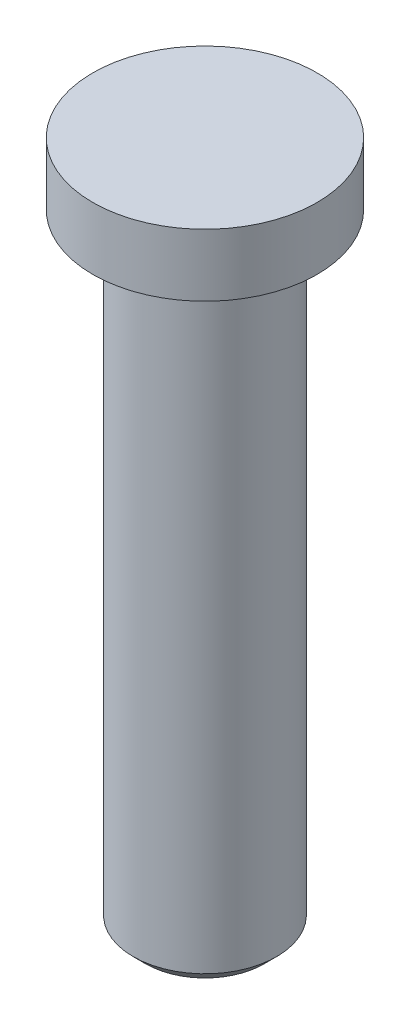
SolidWorks part; units mm, degrees
ref_plane "Front Plane" through (0, 0, 0) normal (0, 0, 1) x (1, 0, 0)
ref_plane "Top Plane" through (0, 0, 0) normal (0, 1, 0) x (1, 0, 0)
ref_plane "Right Plane" through (0, 0, 0) normal (1, 0, 0) x (0, 0, -1)
sketch "Sketch1" plane through (0, 0, 0) normal (0, 1, 0) x (1, 0, 0)
  circle A0 centre (0, 0) radius 0.575
  dimension "D1" = 1.15
extrude "Boss-Extrude1" add sketch "Sketch1" along normal blind 5
sketch "Sketch2" plane through (0, 5, 0) normal (0, 1, 0) x (1, 0, 0)
  circle A0 centre (0, 0) radius 0.9
  dimension "D1" = 1.8
extrude "Boss-Extrude2" add sketch "Sketch2" along normal blind 0.5
chamfer "Chamfer1" distance 0.1 angle 45 1 edges at (0, 0, 0.575)
